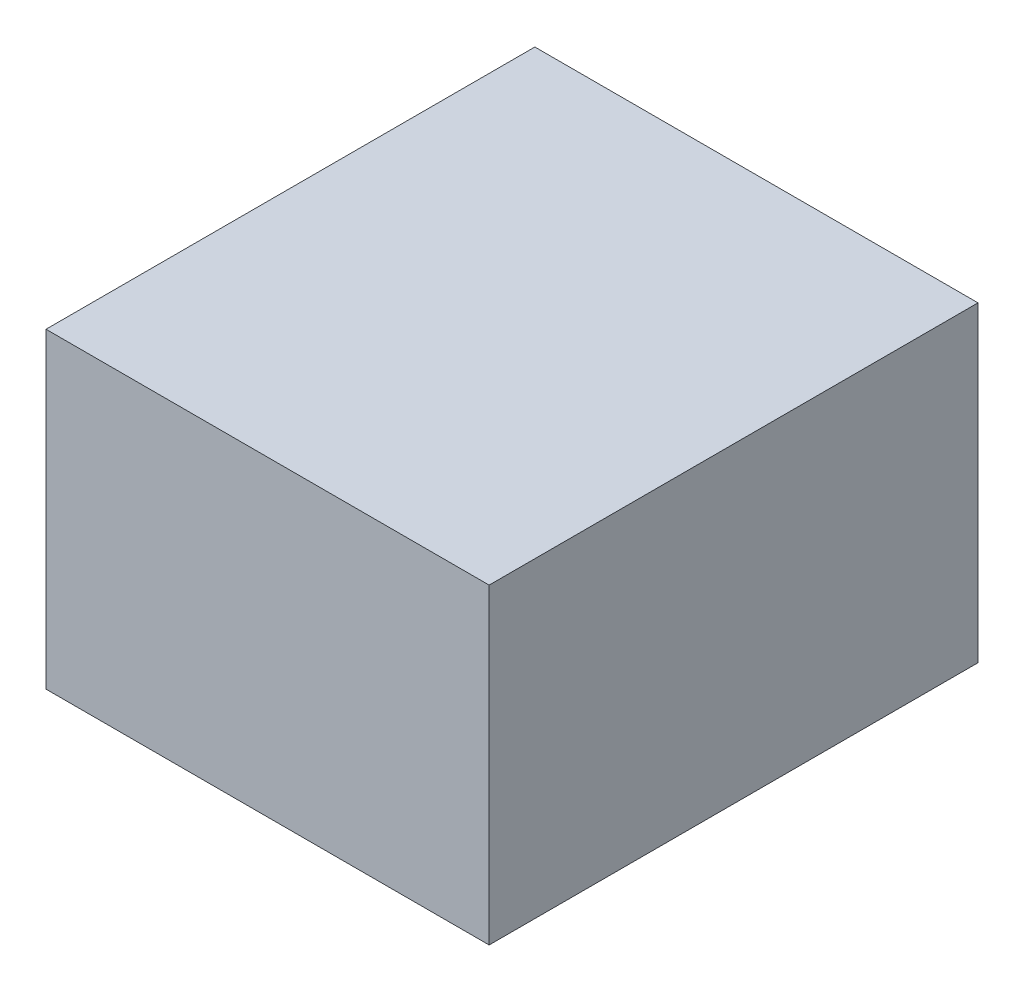
SolidWorks part; units mm, degrees
ref_plane "Front Plane" through (0, 0, 0) normal (0, 0, 1) x (1, 0, 0)
ref_plane "Top Plane" through (0, 0, 0) normal (0, 1, 0) x (1, 0, 0)
ref_plane "Right Plane" through (0, 0, 0) normal (1, 0, 0) x (0, 0, -1)
sketch "Sketch1" plane through (0, 0, 0) normal (0, 1, 0) x (1, 0, 0)
  line L1 (0, 0) -> (2.8434, 0)
  line L2 (0, 0) -> (0, -3.1368)
  line L3 (0, -3.1368) -> (2.8434, -3.1368)
  line L4 (2.8434, 0) -> (2.8434, -3.1368)
extrude "Boss-Extrude1" add sketch "Sketch1" along normal blind 2
